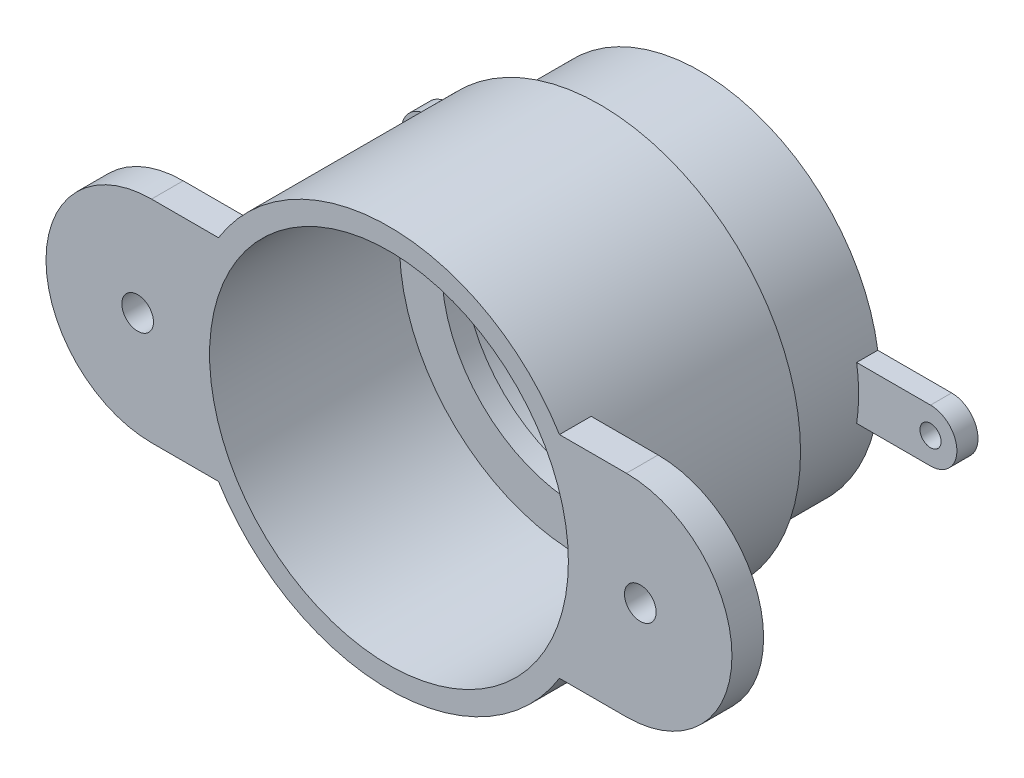
SolidWorks part; units mm, degrees
ref_plane "前视基准面" through (0, 0, 0) normal (0, 0, 1) x (1, 0, 0)
ref_plane "上视基准面" through (0, 0, 0) normal (0, 1, 0) x (1, 0, 0)
ref_plane "右视基准面" through (0, 0, 0) normal (1, 0, 0) x (0, 0, -1)
sketch "草图1" plane through (0, 0, 0) normal (0, 0, 1) x (1, 0, 0)
  circle A1 centre (0, 0) radius 19
  dimension "D1" = 38
extrude "凸台-拉伸1" add sketch "草图1" along normal blind 20
sketch "草图3" plane through (0, 0, 20) normal (0, 0, 1) x (1, 0, 0)
  line L0 (0, 0) -> (0, 10) construction
  line L1 (-22.5, 10) -> (22.5, 10)
  line L3 (22.5, 0) -> (0, 0) construction
  line L4 (-22.5, -10) -> (22.5, -10)
  arc A0 (22.5, -10) -> (22.5, 10) centre (22.5, 0) ccw
  arc A1 (-22.5, 10) -> (-22.5, -10) centre (-22.5, 0) ccw
  point P9 (0, -10)
  dimension "D1" = 22.5
  dimension "D2" = 10
extrude "凸台-拉伸2" add sketch "草图3" against normal blind 3
sketch "草图6" plane through (0, 0, 20) normal (0, 0, 1) x (1, 0, 0)
  circle A0 centre (0, 0) radius 17
  dimension "D1" = 34
extrude "切除-拉伸1" cut sketch "草图6" against normal blind 18
sketch "草图7" plane through (0, 0, 0) normal (0, 0, -1) x (-1, 0, 0)
  circle A0 centre (0, 0) radius 17
  circle A1 centre (0, 0) radius 15
  dimension "D1" = 34
  dimension "D2" = 30
extrude "凸台-拉伸3" add sketch "草图7" along normal blind 9.5
sketch "草图8" plane through (0, 0, 0) normal (0, 0, -1) x (-1, 0, 0)
  circle A0 centre (0, 0) radius 13
  dimension "D1" = 26
extrude "切除-拉伸2" cut sketch "草图8" against normal up to next
sketch "草图10" plane through (0, 0, -9.5) normal (0, 0, -1) x (-1, 0, 0)
  line L0 (-16.8152, 2.5) -> (-23.8152, 2.5)
  line L2 (-23.8152, 0) -> (-17, 0) construction
  line L3 (-16.8152, -2.5) -> (-23.8152, -2.5)
  line L4 (0, 0) -> (0, 16) construction
  line L5 (16.8152, 2.5) -> (23.8152, 2.5)
  line L6 (16.8152, -2.5) -> (23.8152, -2.5)
  circle A0 centre (0, 0) radius 17 construction
  circle A1 centre (0, 0) radius 17 construction
  arc A2 (-16.8152, 2.5) -> (-16.8152, -2.5) centre (0, 0) ccw
  arc A3 (16.8152, -2.5) -> (16.8152, 2.5) centre (0, 0) ccw
  arc A4 (-23.8152, 2.5) -> (-23.8152, -2.5) centre (-23.8152, 0) ccw
  arc A6 (23.8152, 2.5) -> (23.8152, -2.5) centre (23.8152, 0) cw
  dimension "D1" = 7
  dimension "D2" = 2.5
  dimension "D3" = 16
extrude "凸台-拉伸4" add sketch "草图10" against normal blind 2
sketch "草图13" plane through (0, 0, 17) normal (0, 0, -1) x (-1, 0, 0)
  circle A0 centre (-23.8152, 0) radius 5 construction
  point P0 (-23.8152, 0)
  dimension "D1" = 10
sketch "草图14" plane through (0, 0, -9.5) normal (0, 0, -1) x (-1, 0, 0)
  circle A0 centre (-23.8152, 0) radius 1
  dimension "D1" = 2
extrude "切除-拉伸3" cut sketch "草图14" against normal up to next
sketch "草图15" plane through (0, 0, 17) normal (0, 0, -1) x (-1, 0, 0)
  circle A0 centre (-23.8152, 0) radius 1.5
  dimension "D1" = 3
extrude "切除-拉伸4" cut sketch "草图15" against normal up to next
mirror "镜向1" about plane through (0, 0, 0) normal (1, 0, 0) of "切除-拉伸3", "切除-拉伸4"
